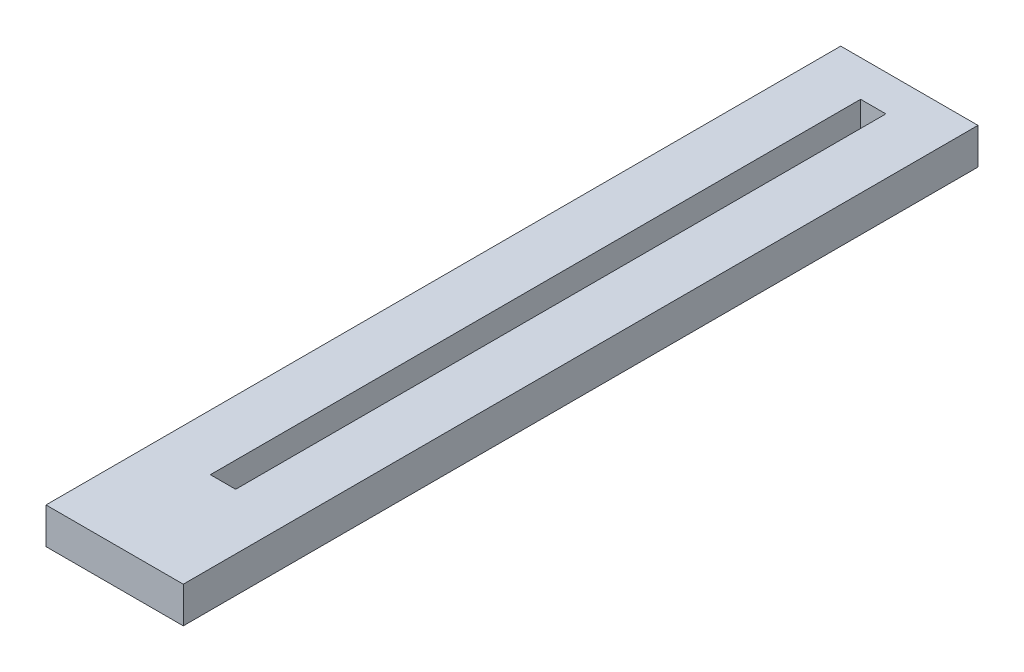
SolidWorks part; units mm, degrees
ref_plane "Front Plane" through (0, 0, 0) normal (0, 0, 1) x (1, 0, 0)
ref_plane "Top Plane" through (0, 0, 0) normal (0, 1, 0) x (1, 0, 0)
ref_plane "Right Plane" through (0, 0, 0) normal (1, 0, 0) x (0, 0, -1)
sketch "Sketch1" plane through (0, 0, 0) normal (0, 1, 0) x (1, 0, 0)
  line L1 (0, 0) -> (-19, 0)
  line L2 (0, 0) -> (0, 110)
  line L3 (0, 110) -> (-19, 110)
  line L4 (-19, 0) -> (-19, 110)
  line L5 (-11.25, 105) -> (-7.75, 105)
  line L6 (-11.25, 105) -> (-11.25, 15)
  line L7 (-11.25, 15) -> (-7.75, 15)
  line L8 (-7.75, 105) -> (-7.75, 15)
  point P9 (-9.5, 105)
  point P10 (-9.5, 110)
  dimension "D1" = 110
  dimension "D2" = 19
  dimension "D3" = 3.5
  dimension "D4" = 5
  dimension "D5" = 90
extrude "Boss-Extrude1" add sketch "Sketch1" along normal blind 5
